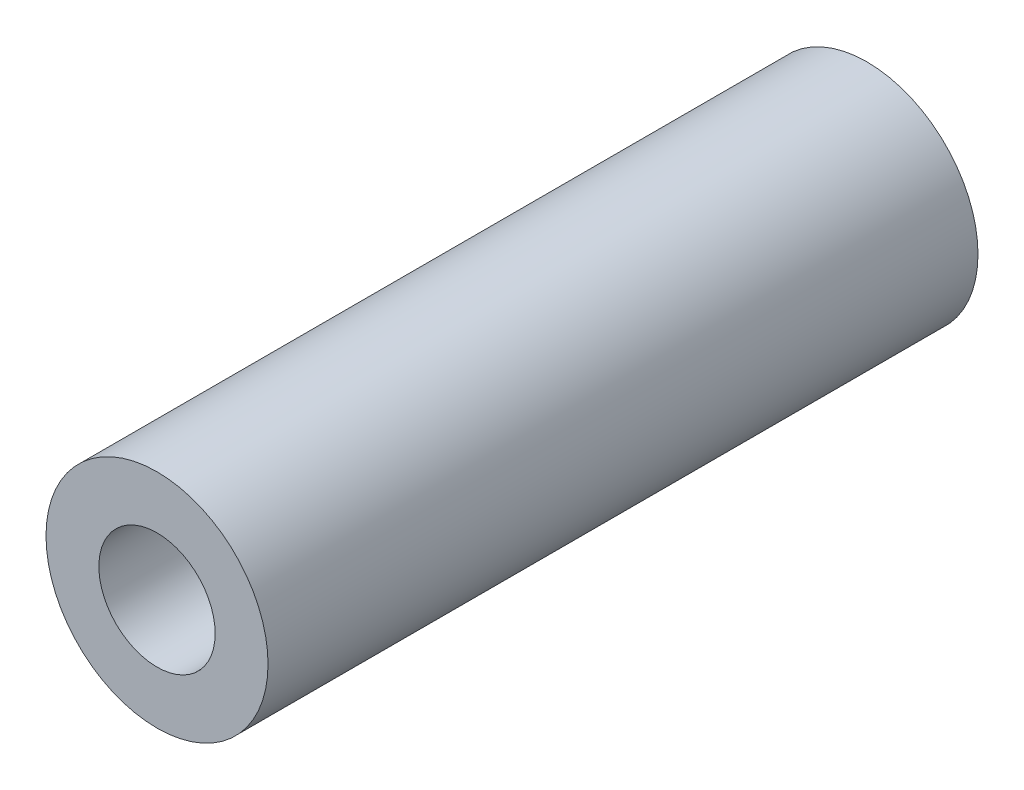
SolidWorks part; units mm, degrees
ref_plane "Front Plane" through (0, 0, 0) normal (0, 0, 1) x (1, 0, 0)
ref_plane "Top Plane" through (0, 0, 0) normal (0, 1, 0) x (1, 0, 0)
ref_plane "Right Plane" through (0, 0, 0) normal (1, 0, 0) x (0, 0, -1)
sketch "Sketch1" plane through (0, 0, 0) normal (0, 0, 1) x (1, 0, 0)
  circle A0 centre (0, 0) radius 1.1
  circle A1 centre (0, 0) radius 2.1
  dimension "D1" = 2.2
  dimension "D2" = 4.2
extrude "Boss-Extrude1" add sketch "Sketch1" along normal blind 13.43
